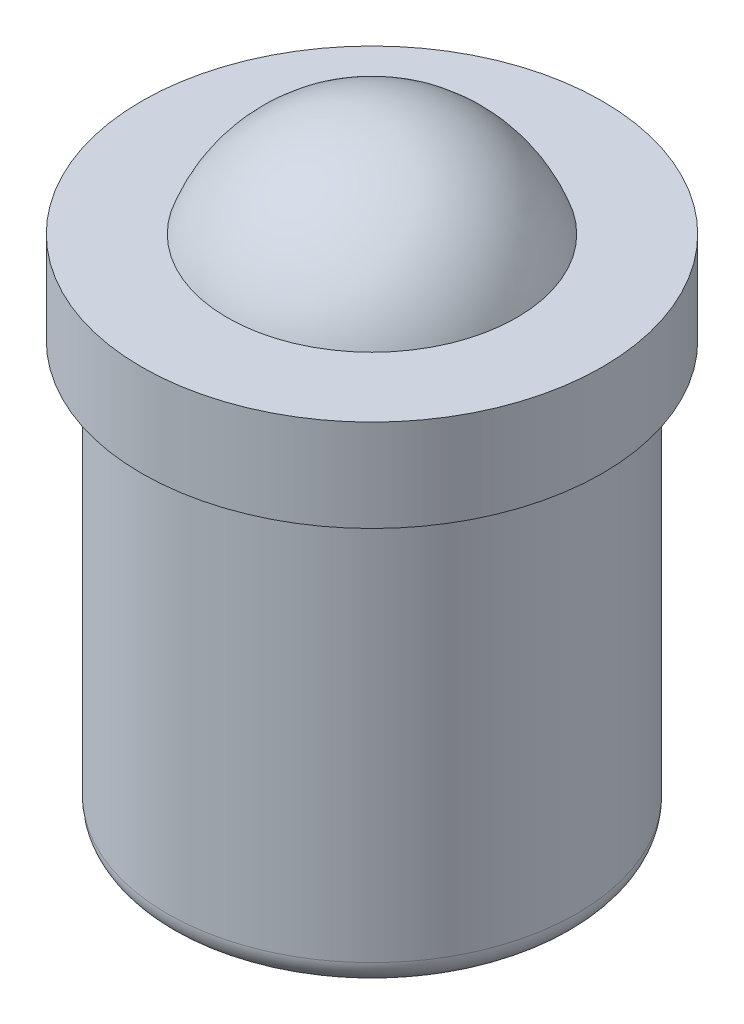
SolidWorks part; units mm, degrees
ref_plane "Front Plane" through (0, 0, 0) normal (0, 0, 1) x (1, 0, 0)
ref_plane "Top Plane" through (0, 0, 0) normal (0, 1, 0) x (1, 0, 0)
ref_plane "Right Plane" through (0, 0, 0) normal (1, 0, 0) x (0, 0, -1)
sketch "Sketch1" plane through (0, 0, 0) normal (0, 0, 1) x (1, 0, 0)
  line L0 (0, 0) -> (-2, 0)
  line L1 (-2, 0) -> (-2, 4.1)
  line L2 (-2, 4.1) -> (-2.25, 4.1)
  line L3 (-2.25, 4.1) -> (-2.25, 5)
  line L4 (-2.25, 5) -> (-1.4142, 5)
  line L5 (0, 6) -> (0, 0)
  arc A0 (-1.4142, 5) -> (0, 6) centre (0, 4.5) cw
  point P9 (0, 0)
  point P10 (-2.25, 4.55)
  point P11 (0, 6)
  dimension "D4" = 1.5
  dimension "D1" = 2
  dimension "D2" = 5
  dimension "D3" = 0.9
  dimension "D5" = 2.25
  dimension "D6" = 1
revolve "Revolve1" add sketch "Sketch1" angle 360 about L5
fillet "Fillet1" radius 0.25 1 edges at (-2, 0, 0)
